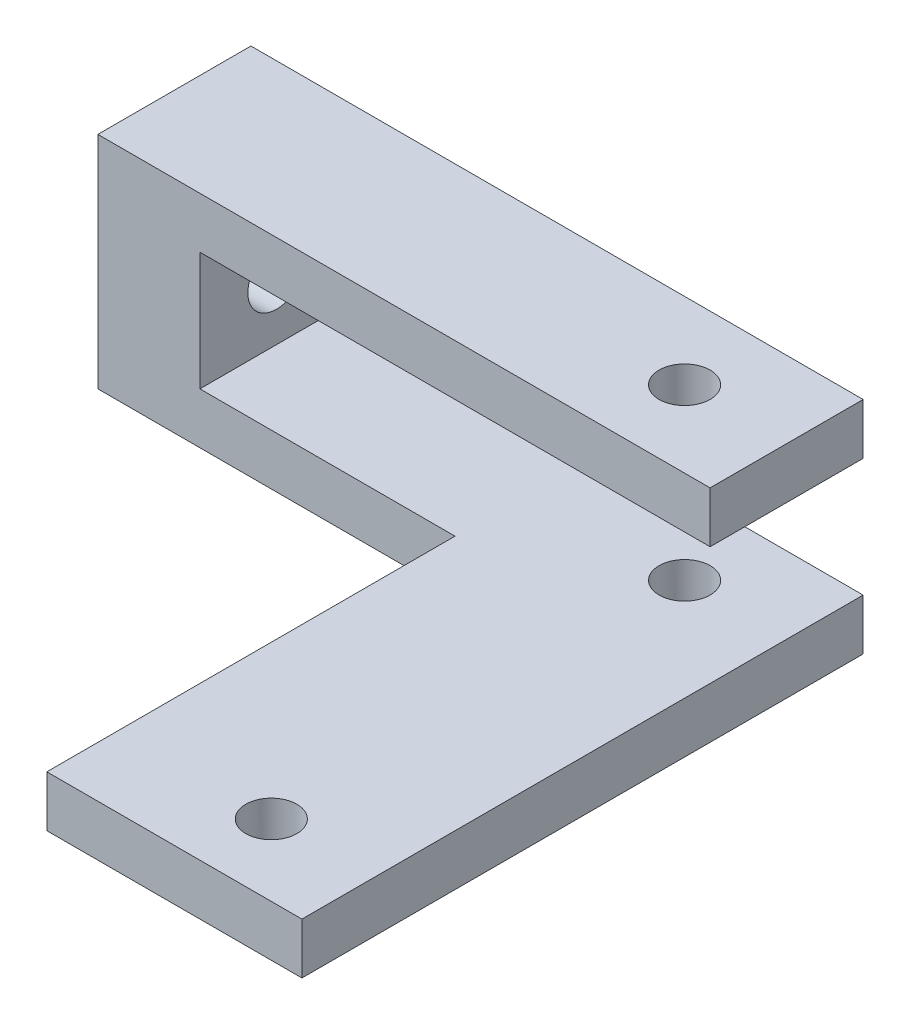
SolidWorks part; units mm, degrees
ref_plane "Front Plane" through (0, 0, 0) normal (0, 0, 1) x (1, 0, 0)
ref_plane "Top Plane" through (0, 0, 0) normal (0, 1, 0) x (1, 0, 0)
ref_plane "Right Plane" through (0, 0, 0) normal (1, 0, 0) x (0, 0, -1)
sketch "Sketch1" plane through (0, 0, 0) normal (0, 0, 1) x (1, 0, 0)
  line L0 (0, 0) -> (76.2, 0)
  line L13 (0, 0) -> (0, -27.432)
  line L14 (0, -27.432) -> (76.2, -27.432)
  line L15 (76.2, -21.082) -> (76.2, -27.432)
  line L16 (76.2, 0) -> (76.2, -6.35)
  line L17 (12.7, -6.35) -> (76.2, -6.35)
  line L18 (12.7, -21.082) -> (76.2, -21.082)
  line L19 (12.7, -6.35) -> (12.7, -21.082)
  dimension "D1" = 6.35
  dimension "D2" = 14.732
  dimension "D3" = 6.35
extrude "Boss-Extrude1" add sketch "Sketch1" along normal blind 19.05
sketch "Sketch2" plane through (0, 0, 19.05) normal (0, 0, 1) x (1, 0, 0)
  line L0 (76.2, -21.082) -> (12.7, -21.082) construction
  line L1 (44.45, -21.082) -> (76.2, -21.082)
  line L2 (44.45, -21.082) -> (44.45, -27.432)
  line L3 (44.45, -27.432) -> (76.2, -27.432)
  line L4 (76.2, -21.082) -> (76.2, -27.432)
extrude "Boss-Extrude2" add sketch "Sketch2" along normal blind 50.8
sketch "Sketch3" plane through (0, -21.082, 0) normal (0, 1, 0) x (1, 0, 0)
  circle A0 centre (63.5, -60.96) radius 3.175
  circle A1 centre (63.5, -9.525) radius 3.175
extrude "Cut-Extrude1" cut sketch "Sketch3" against normal through all both and the other way through all
sketch "Sketch4" plane through (0, 0, 0) normal (-1, 0, 0) x (0, 0, 1)
  circle A1 centre (9.525, -13.716) radius 3.556
  point P2 (0, 0)
extrude "Cut-Extrude2" cut sketch "Sketch4" against normal blind 50.8
